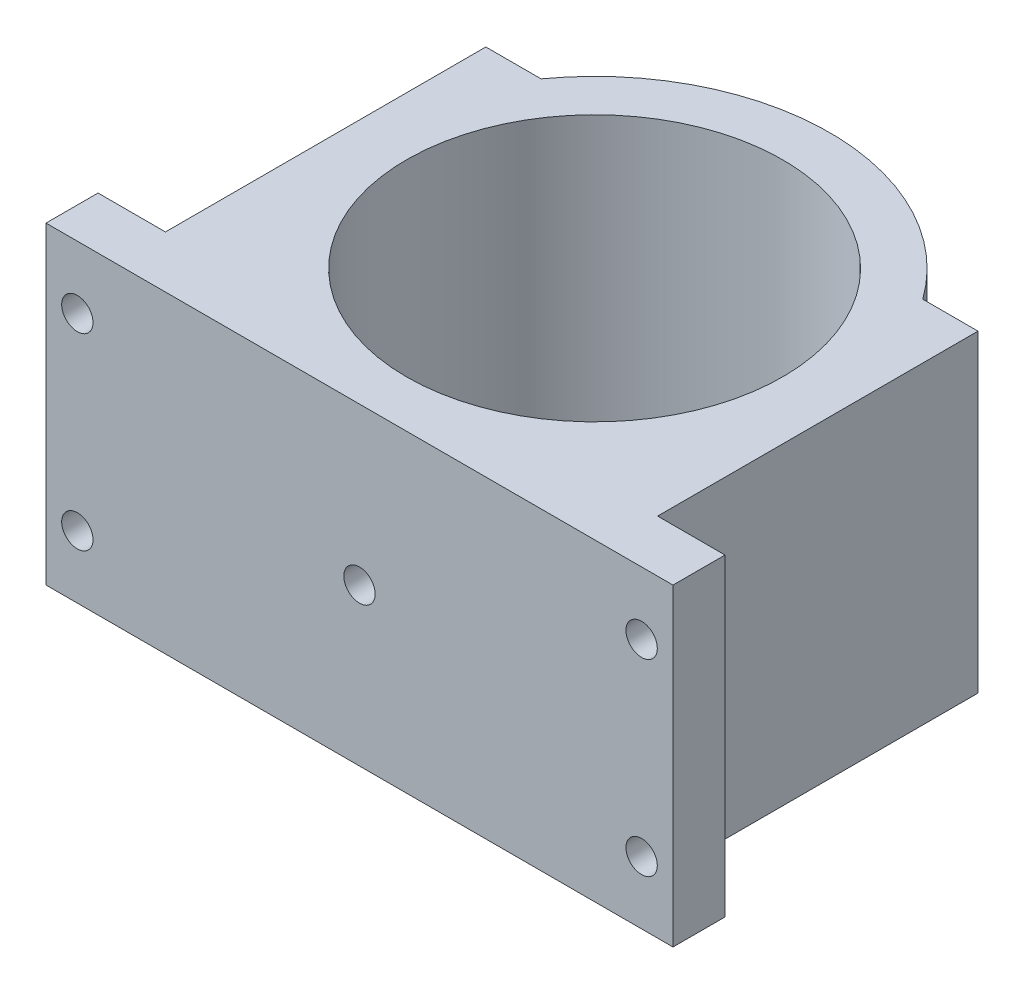
SolidWorks part; units mm, degrees
ref_plane "Front Plane" through (0, 0, 0) normal (0, 0, 1) x (1, 0, 0)
ref_plane "Top Plane" through (0, 0, 0) normal (0, 1, 0) x (1, 0, 0)
ref_plane "Right Plane" through (0, 0, 0) normal (1, 0, 0) x (0, 0, -1)
sketch "Sketch1" plane through (0, 0, 0) normal (0, 1, 0) x (1, 0, 0)
  line L0 (-100, -75) -> (100, -75)
  line L1 (-100, -75) -> (-100, -58.4)
  line L2 (-100, -58.4) -> (-78.5, -58.4)
  line L3 (-78.5, -58.4) -> (-78.5, 0)
  line L4 (0, 0) -> (0, -75) construction
  line L5 (-78.5, 0) -> (-78.5, 43.8)
  line L6 (100, -75) -> (100, -58.4)
  line L7 (100, -58.4) -> (78.5, -58.4)
  line L8 (78.5, 0) -> (78.5, 43.8)
  line L9 (78.5, -58.4) -> (78.5, 0)
  line L10 (-78.5, 43.8) -> (-60.8815, 43.8)
  line L11 (78.5, 43.8) -> (60.8815, 43.8)
  circle A0 centre (0, 0) radius 60
  arc A2 (-60.8815, 43.8) -> (60.8815, 43.8) centre (0, 0) cw
  dimension "D1" = 120
  dimension "D3" = 75
  dimension "D8" = 75
  dimension "D2" = 200
  dimension "D4" = 16.6
  dimension "D5" = 100
  dimension "D6" = 78.5
  dimension "D7" = 43.8
extrude "Boss-Extrude1" add sketch "Sketch1" along normal blind 100
sketch "Sketch2" plane through (0, 0, 75) normal (0, 0, 1) x (1, 0, 0)
  line L0 (0, 100) -> (0, 0) construction
  line L1 (-100, 100) -> (100, 100) construction
  line L2 (-100, 100) -> (-100, 0) construction
  point P0 (-90, 80)
  point P1 (-90, 20)
  point P9 (90, 20)
  point P10 (90, 80)
  dimension "D1" = 10
  dimension "D2" = 20
  dimension "D3" = 60
hole_wizard "M8 Clearance Hole1" positions "Sketch2" profile "Sketch3" hole size "M8" standard "ANSI Metric" end condition through all
sketch "Sketch3" plane through (-90, 80, 75) normal (1, 0, 0) x (0, -1, 0)
  line L0 (0, 0) -> (0, 150)
  line L1 (0, 150) -> (5, 150)
  line L2 (5, 150) -> (5, 0)
  line L5 (5, 0) -> (0, 0)
  line L11 (0, -6.35) -> (0, 107.95) construction
  dimension "Thru Hole Dia." = 10
  dimension "Thru Hole Depth" = 150
sketch "Sketch4" plane through (0, 0, 75) normal (0, 0, 1) x (1, 0, 0)
  line L0 (-100, 100) -> (100, 100) construction
  line L1 (100, 100) -> (100, 0) construction
  point P0 (0, 50)
  dimension "D1" = 50
  dimension "D2" = 100
hole_wizard "Ø10.0mm Dowel Hole1" positions "Sketch4" profile "Sketch5" hole size "Ø10.0" standard "ANSI Metric"
sketch "Sketch5" plane through (0, 50, 75) normal (1, 0, 0) x (0, -1, 0)
  line L0 (0, 0) -> (0, 11.0043)
  line L1 (0, 11.0043) -> (5, 8)
  line L2 (5, 8) -> (5, 0)
  line L5 (5, 0) -> (0, 0)
  line L10 (0, 11.0043) -> (-5, 8) construction
  line L11 (0, -6.35) -> (0, 107.95) construction
  dimension "Hole Dia." = 10
  dimension "Hole Depth" = 8
  dimension "Drill Angle" = 118
